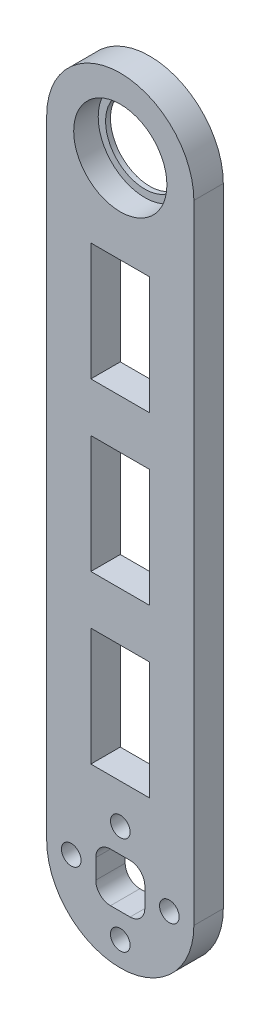
SolidWorks part; units mm, degrees
ref_plane "前视基准面" through (0, 0, 0) normal (0, 0, 1) x (1, 0, 0)
ref_plane "上视基准面" through (0, 0, 0) normal (0, 1, 0) x (1, 0, 0)
ref_plane "右视基准面" through (0, 0, 0) normal (1, 0, 0) x (0, 0, -1)
sketch "草图1" plane through (0, 0, 0) normal (0, 0, 1) x (1, 0, 0)
  line L2 (-15, -64) -> (-15, 64)
  line L4 (15, -64) -> (15, 64)
  line L5 (-15, -64) -> (15, 64) construction
  line L6 (-15, 64) -> (15, -64) construction
  circle A0 centre (0, 64) radius 9.5
  arc A1 (15, 64) -> (-15, 64) centre (0, 64) ccw
  arc A4 (-15, -64) -> (15, -64) centre (0, -64) ccw
  circle A5 centre (0, -64) radius 10 construction
  circle A6 centre (0, -54) radius 2
  circle A7 centre (10, -64) radius 2
  circle A8 centre (0, -74) radius 2
  circle A9 centre (-10, -64) radius 2
  point P0 (0, 0)
  dimension "D2" = 19
  dimension "D4" = 15
  dimension "D5" = 15
  dimension "D6" = 20
  dimension "D7" = 4
  dimension "D1" = 128
  dimension "D3" = 30
  dimension "D8" = 4
extrude "凸台-拉伸1" add sketch "草图1" along normal blind 6
sketch "草图2" plane through (0, 0, 6) normal (0, 0, 1) x (1, 0, 0)
  line L0 (0, -1000) -> (0, 49000) construction
  line L2 (-6, 46) -> (6, 46)
  line L3 (-6, 46) -> (-6, 22)
  line L4 (-6, 22) -> (6, 22)
  line L5 (6, 46) -> (6, 22)
  line L6 (-6, 46) -> (6, 22) construction
  line L7 (-6, 22) -> (6, 46) construction
  line L8 (-6, 12) -> (6, 12)
  line L9 (-6, 12) -> (-6, -12)
  line L10 (-6, -12) -> (6, -12)
  line L11 (6, 12) -> (6, -12)
  line L12 (-6, 12) -> (6, -12) construction
  line L13 (-6, -12) -> (6, 12) construction
  line L14 (-6, -22) -> (6, -22)
  line L15 (-6, -22) -> (-6, -46)
  line L16 (-6, -46) -> (6, -46)
  line L17 (6, -22) -> (6, -46)
  line L18 (-6, -22) -> (6, -46) construction
  line L19 (-6, -46) -> (6, -22) construction
  line L20 (-5, -69) -> (5, -69)
  line L21 (-5, -69) -> (-5, -59)
  line L22 (-5, -59) -> (5, -59)
  line L23 (5, -69) -> (5, -59)
  line L24 (-5, -69) -> (5, -59) construction
  line L25 (-5, -59) -> (5, -69) construction
  point P1 (0, 34)
  point P8 (0, 0)
  point P13 (0, -34)
  point P18 (0, -64)
  dimension "D1" = 24
  dimension "D2" = 12
  dimension "D3" = 24
  dimension "D4" = 12
  dimension "D5" = 24
  dimension "D6" = 12
  dimension "D7" = 10
  dimension "D8" = 10
  dimension "D9" = 10
  dimension "D10" = 10
extrude "切除-拉伸1" cut sketch "草图2" against normal blind 6
fillet "圆角1" radius 3 4 edges at (-5, -69, 3) (5, -69, 3) (5, -59, 3) (-5, -59, 3)
sketch "草图3" plane through (0, 0, 0) normal (0, 0, -1) x (-1, 0, 0)
  circle A1 centre (0, 64) radius 8
  circle A2 centre (0, 64) radius 9.5
  dimension "D1" = 19
  dimension "D2" = 16
extrude "凸台-拉伸3" add sketch "草图3" against normal blind 1
